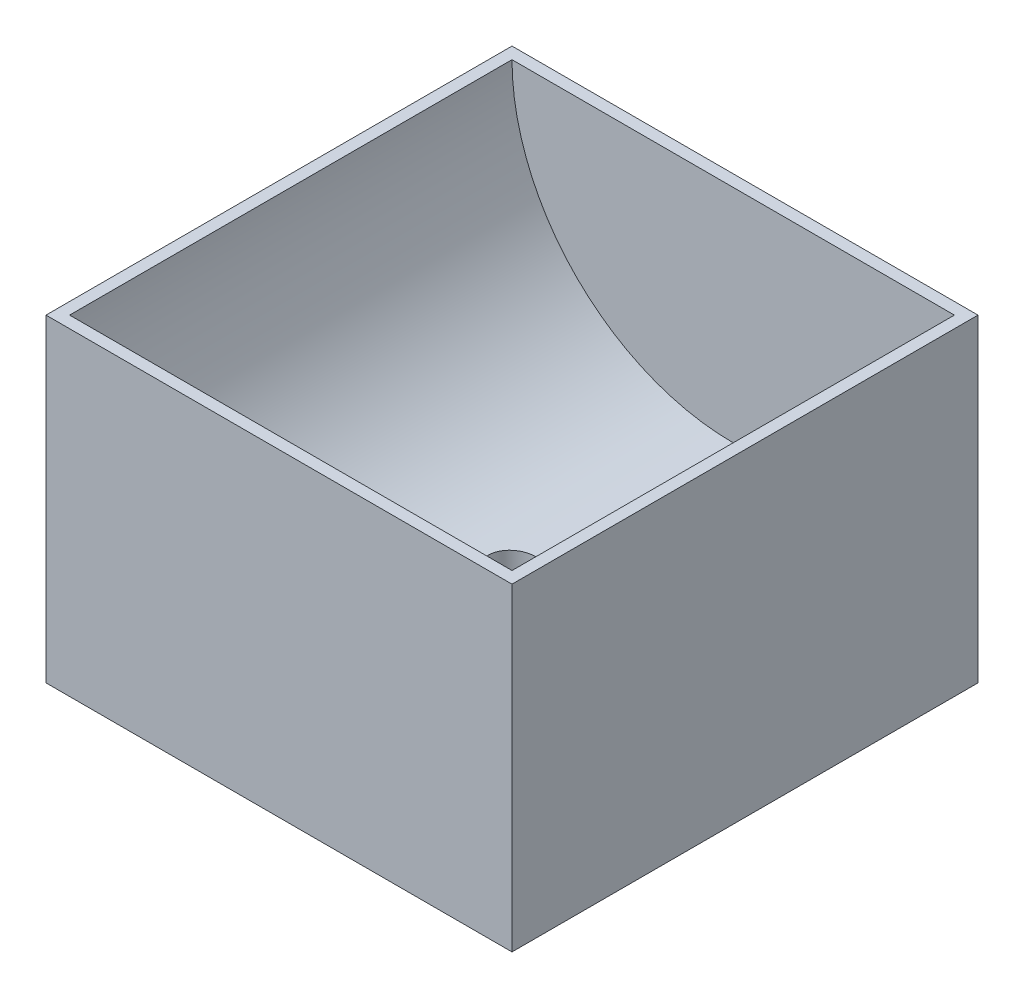
SolidWorks part; units mm, degrees
ref_plane "Front Plane" through (0, 0, 0) normal (0, 0, 1) x (1, 0, 0)
ref_plane "Top Plane" through (0, 0, 0) normal (0, 1, 0) x (1, 0, 0)
ref_plane "Right Plane" through (0, 0, 0) normal (1, 0, 0) x (0, 0, -1)
sketch "Sketch1" plane through (0, 0, 0) normal (0, 0, 1) x (1, 0, 0)
  line L0 (37.5, 0) -> (39.5, 0)
  line L1 (-39.5, 0) -> (-37.5, 0)
  line L2 (-39.5, 0) -> (-39.5, -40.5)
  line L3 (-39.5, -40.5) -> (39.5, -40.5)
  line L4 (39.5, 0) -> (39.5, -40.5)
  arc A0 (-37.5, 0) -> (37.5, 0) centre (0, 0) ccw
  dimension "D1" = 75
  dimension "D2" = 2
  dimension "D3" = 2
  dimension "D4" = 3
extrude "Boss-Extrude1" add sketch "Sketch1" along normal mid plane 75
sketch "Sketch2" plane through (0, 0, 37.5) normal (0, 0, 1) x (1, 0, 0)
  line L1 (-39.5, 0) -> (39.5, 0)
  line L2 (-39.5, 0) -> (-39.5, -40.5)
  line L3 (-39.5, -40.5) -> (39.5, -40.5)
  line L4 (39.5, 0) -> (39.5, -40.5)
extrude "Boss-Extrude2" add sketch "Sketch2" along normal blind 2
sketch "Sketch3" plane through (0, 0, -37.5) normal (0, 0, -1) x (-1, 0, 0)
  line L1 (-39.5, 0) -> (39.5, 0)
  line L2 (-39.5, 0) -> (-39.5, -40.5)
  line L3 (-39.5, -40.5) -> (39.5, -40.5)
  line L4 (39.5, 0) -> (39.5, -40.5)
extrude "Boss-Extrude3" add sketch "Sketch3" along normal blind 2
sketch "Sketch4" plane through (0, -40.5, 0) normal (0, -1, 0) x (1, 0, 0)
  circle A0 centre (0, 0) radius 4.05
  dimension "D1" = 8.1
extrude "Cut-Extrude2" cut sketch "Sketch4" against normal through all
sketch "Sketch5" plane through (0, -40.5, 0) normal (0, -1, 0) x (1, 0, 0)
  line L1 (-7.5056, 0) -> (-3.7528, -6.5)
  line L2 (-3.7528, -6.5) -> (3.7528, -6.5)
  line L3 (3.7528, -6.5) -> (7.5056, 0)
  line L4 (7.5056, 0) -> (3.7528, 6.5)
  line L5 (3.7528, 6.5) -> (-3.7528, 6.5)
  line L6 (-3.7528, 6.5) -> (-7.5056, 0)
  line L7 (-39.5, -39.5) -> (39.5, -39.5)
  line L8 (-39.5, -39.5) -> (-39.5, 39.5)
  line L9 (-39.5, 39.5) -> (39.5, 39.5)
  line L10 (39.5, -39.5) -> (39.5, 39.5)
  circle A0 centre (0, 0) radius 6.5 construction
  dimension "D1" = 13
extrude "Boss-Extrude4" add sketch "Sketch5" along normal blind 13.5
sketch "Sketch6" plane through (0, -54, 0) normal (0, -1, 0) x (1, 0, 0)
  circle A0 centre (0, 0) radius 8
  dimension "D1" = 16
extrude "Cut-Extrude3" cut sketch "Sketch6" against normal blind 7
